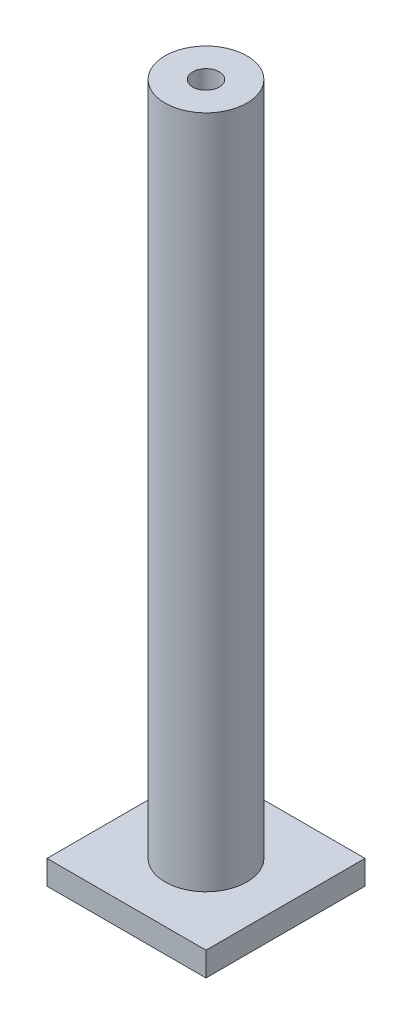
SolidWorks part; units mm, degrees
ref_plane "Front Plane" through (0, 0, 0) normal (0, 0, 1) x (1, 0, 0)
ref_plane "Top Plane" through (0, 0, 0) normal (0, 1, 0) x (1, 0, 0)
ref_plane "Right Plane" through (0, 0, 0) normal (1, 0, 0) x (0, 0, -1)
sketch "Sketch1" plane through (0, 0, 0) normal (0, 1, 0) x (1, 0, 0)
  line L0 (-7.7945, 6.8328) -> (8.7055, -9.6672) construction
  line L1 (-7.7945, 6.8328) -> (8.7055, 6.8328)
  line L2 (-7.7945, 6.8328) -> (-7.7945, -9.6672)
  line L3 (-7.7945, -9.6672) -> (8.7055, -9.6672)
  line L4 (8.7055, 6.8328) -> (8.7055, -9.6672)
  circle A0 centre (0.4555, -1.4172) radius 1.375
  circle A1 centre (0.4555, -1.4172) radius 4.25 construction
  dimension "D2" = 2.75
  dimension "D3" = 8.5
  dimension "D1" = 16.5
extrude "Boss-Extrude1" add sketch "Sketch1" along normal blind 2.5
sketch "Sketch2" plane through (0, 2.5, 0) normal (0, 1, 0) x (1, 0, 0)
  circle A0 centre (0.4555, -1.4172) radius 4.25 construction
  circle A1 centre (0.4555, -1.4172) radius 4.25
  circle A2 centre (0.4555, -1.4172) radius 1.375 construction
  circle A3 centre (0.4555, -1.4172) radius 1.375
extrude "Boss-Extrude2" add sketch "Sketch2" along normal blind 70
